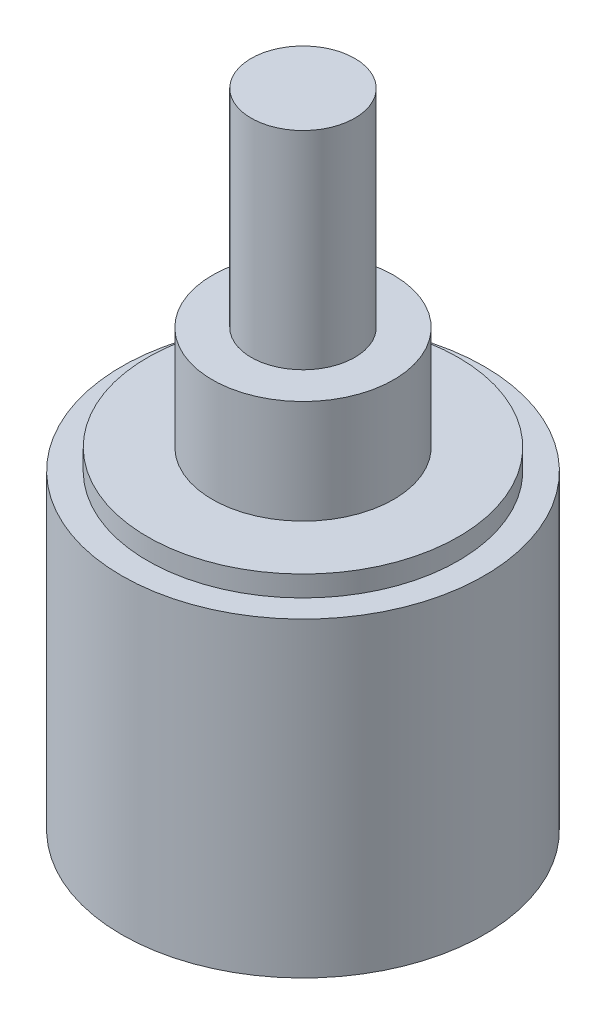
SolidWorks part; units mm, degrees
ref_plane "Front Plane" through (0, 0, 0) normal (0, 0, 1) x (1, 0, 0)
ref_plane "Top Plane" through (0, 0, 0) normal (0, 1, 0) x (1, 0, 0)
ref_plane "Right Plane" through (0, 0, 0) normal (1, 0, 0) x (0, 0, -1)
sketch "Sketch1" plane through (0, 0, 0) normal (0, 0, 1) x (1, 0, 0)
  line L0 (0, 0) -> (0, 35.56) construction
  line L1 (11.1125, 19.05) -> (9.525, 19.05)
  line L2 (9.525, 19.05) -> (9.525, 20.32)
  line L3 (0, 0) -> (11.1125, 0)
  line L4 (11.1125, 19.05) -> (11.1125, 0)
  line L5 (9.525, 20.32) -> (5.5562, 20.32)
  line L6 (5.5562, 20.32) -> (5.5562, 26.67)
  line L7 (0, 39.37) -> (3.175, 39.37)
  line L8 (3.175, 26.67) -> (3.175, 39.37)
  line L9 (5.5562, 26.67) -> (3.175, 26.67)
  line L10 (0, 39.37) -> (0, 0)
  dimension "D1" = 22.225
  dimension "D2" = 6.35
  dimension "D3" = 12.7
  dimension "D4" = 11.1125
  dimension "D5" = 19.05
  dimension "D6" = 19.05
  dimension "D7" = 1.27
  dimension "D8" = 6.35
revolve "Revolve1" add sketch "Sketch1" angle 360 about L0
